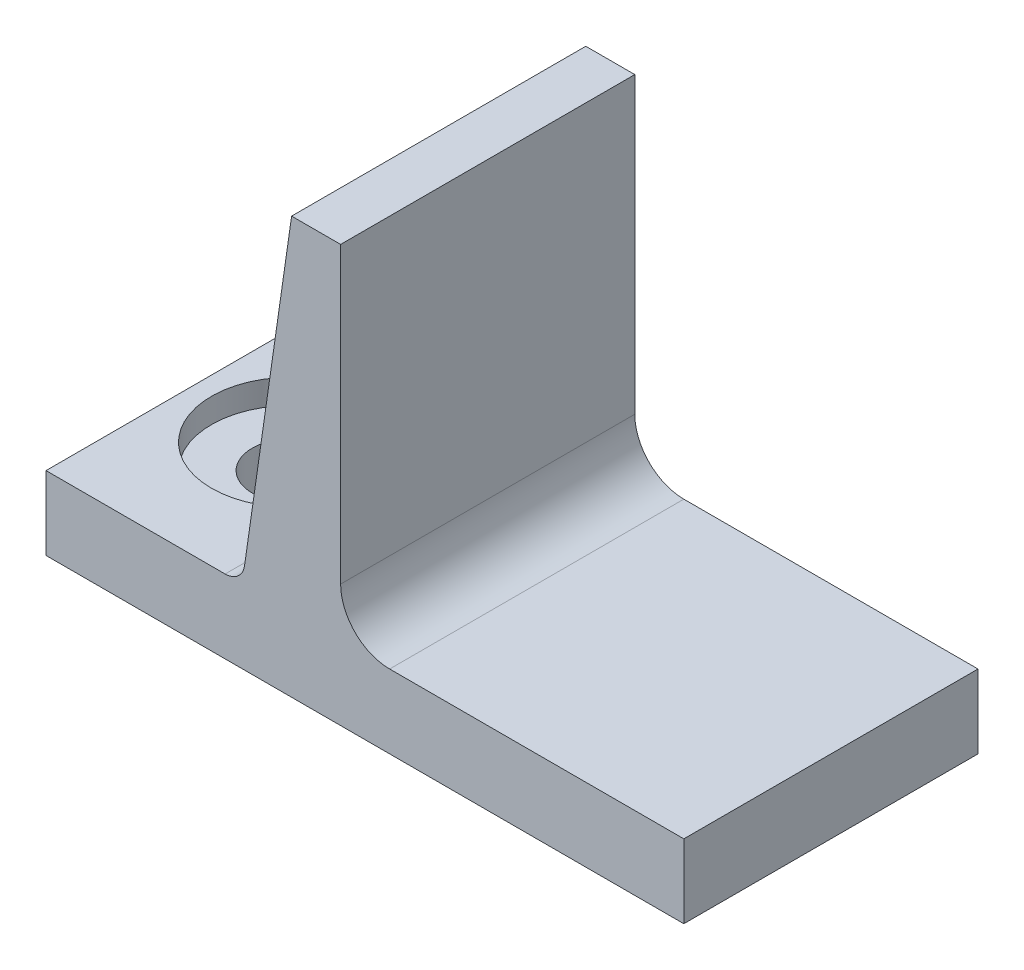
SolidWorks part; units mm, degrees
material "Ti-6Al-2Sn-2Zr-2Mo-2Cr-0.25Si (SS)"
ref_plane "Front Plane" through (0, 0, 0) normal (0, 0, 1) x (1, 0, 0)
ref_plane "Top Plane" through (0, 0, 0) normal (0, 1, 0) x (1, 0, 0)
ref_plane "Right Plane" through (0, 0, 0) normal (1, 0, 0) x (0, 0, -1)
sketch "Sketch1" plane through (0, 0, 0) normal (0, 0, 1) x (1, 0, 0)
  line L0 (0, 0) -> (44.45, 0)
  line L1 (44.45, 0) -> (44.45, -9.525)
  line L2 (44.45, -9.525) -> (-38.1608, -9.525)
  line L3 (-38.1608, -9.525) -> (-38.1608, 0)
  line L4 (-38.1608, 0) -> (-12.7608, 0)
  line L5 (-12.7608, 0) -> (-6.35, 44.45)
  line L6 (-6.35, 44.45) -> (0, 44.45)
  line L7 (0, 44.45) -> (0, 0)
  dimension "D1" = 44.45
  dimension "D2" = 44.45
  dimension "D3" = 9.525
  dimension "D4" = 38.1608
  dimension "D5" = 6.35
  dimension "D6" = 25.4
extrude "Boss-Extrude1" add sketch "Sketch1" along normal blind 38.1
hole_wizard "CBORE for 3/8 Binding Head Machine Screw1" positions "Sketch6" profile "Sketch3" counterbore size "3/8" standard "ANSI Inch" end condition through all
sketch "Sketch6" plane through (0, 0, 0) normal (0, 1, 0) x (1, 0, 0)
  line L0 (-12.7608, 0) -> (-38.1608, 0) construction
  line L1 (-38.1608, -38.1) -> (-38.1608, 0) construction
  point P0 (-25.4608, -19.05)
  point P5 (-25.4608, 0)
  point P8 (-38.1608, -19.05)
sketch "Sketch3" plane through (-25.4608, 0, 19.05) normal (1, 0, 0) x (0, 0, 1)
  line L0 (0, 0) -> (0, 9.525)
  line L1 (0, 9.525) -> (5.0419, 9.525)
  line L3 (5.0419, 9.525) -> (5.0419, 3.175)
  line L4 (10.3187, 3.175) -> (5.0419, 3.175)
  line L5 (10.3187, 3.175) -> (10.3187, 0)
  line L7 (10.3187, 0) -> (0, 0)
  line L11 (0, 0) -> (0, 107.95) construction
  dimension "Thru Hole Dia." = 10.0838
  dimension "Thru Hole Depth" = 9.525
  dimension "C'Bore Depth" = 3.175
fillet "Fillet1" radius 2.54 1 edges at (-12.7608, 0, 19.05)
fillet "Fillet2" radius 6.35 1 edges at (0, 0, 19.05)
